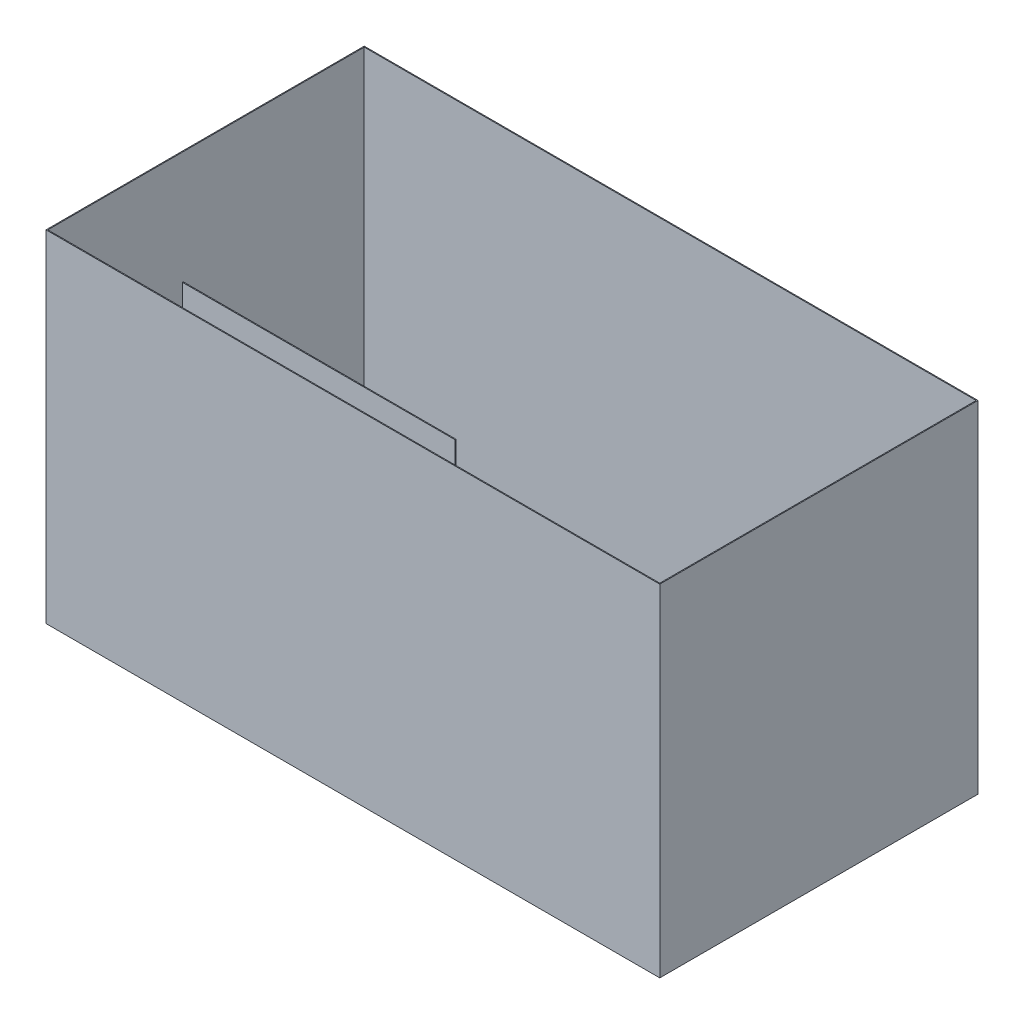
SolidWorks part; units mm, degrees
ref_plane "Спереди" through (0, 0, 0) normal (0, 0, 1) x (1, 0, 0)
ref_plane "Сверху" through (0, 0, 0) normal (0, 1, 0) x (1, 0, 0)
ref_plane "Справа" through (0, 0, 0) normal (1, 0, 0) x (0, 0, -1)
sketch "MASTER_FOOTPRINT" plane through (0, 0, 0) normal (0, 1, 0) x (1, 0, 0)
  line L1 (0, 0) -> (1350, 0)
  line L2 (0, 0) -> (0, 700)
  line L3 (0, 700) -> (1350, 700)
  line L4 (1350, 0) -> (1350, 700)
  dimension "D1" = 1350
  dimension "D2" = 700
extrude "BATH_BASE_PLATE" add sketch "MASTER_FOOTPRINT" along normal blind 750
shell "BATH_SHELL_2MM" thickness 2
sketch "Эскиз1" plane through (0, 0, 0) normal (0, 1, 0) x (1, 0, 0)
  line L1 (50, 250) -> (650, 250)
  line L2 (50, 250) -> (50, 252)
  line L3 (50, 252) -> (650, 252)
  line L4 (650, 250) -> (650, 252)
extrude "DISTRIBUTOR_PANEL_TEST" add sketch "Эскиз1" along normal blind 450 from offset 100 separate body
equation "\"AI_Q_Peak\"= 0.006"
equation "\"AI_B_Bath\"= 700"
equation "\"AI_L_Settle\"= 900"
equation "\"AI_L_Inlet\"= 250"
equation "\"AI_L_Outlet\"= 200"
equation "\"AI_L_Bath\"= 1350"
equation "\"AI_H_Water\"= 550"
equation "\"AI_H_Freeboard\"= 200"
equation "\"AI_H_Bath\"= 750"
equation "\"AI_Shell_Thickness\"= 2"
equation "\"AI_Inlet_DN\"= 100"
equation "\"AI_Weir_Width\"= 600"
equation "\"AI_Inlet_Baffle_Offset\"= 125"
equation "\"AI_Distributor_Open_Area\"= 0.28"
equation "\"AI_Distributor_Hole_Dia\"= 22"
equation "\"AI_Distributor_Blind_Zone\"= 110"
equation "\"AI_Outlet_Baffle_Depth\"= 250"
equation "\"AI_Screw_Diameter\"= 100"
equation "\"AI_Screw_Pitch\"= 100"
equation "\"AI_Screw_Angle\"= 30"
equation "\"AI_Screw_Rpm\"= 15"
equation "\"AI_Screw_Clearance\"= 5"
equation "\"AI_Liner_Thickness\"= 5"
equation "\"AI_Discharge_Height\"= 650"
equation "\"AI_Frame_Height\"= 500"
equation "\"D1@MASTER_FOOTPRINT\" = \"AI_L_Bath\""
equation "\"D2@MASTER_FOOTPRINT\" = \"AI_B_Bath\""
equation "\"D1@BATH_BASE_PLATE\" = \"AI_H_Bath\""
